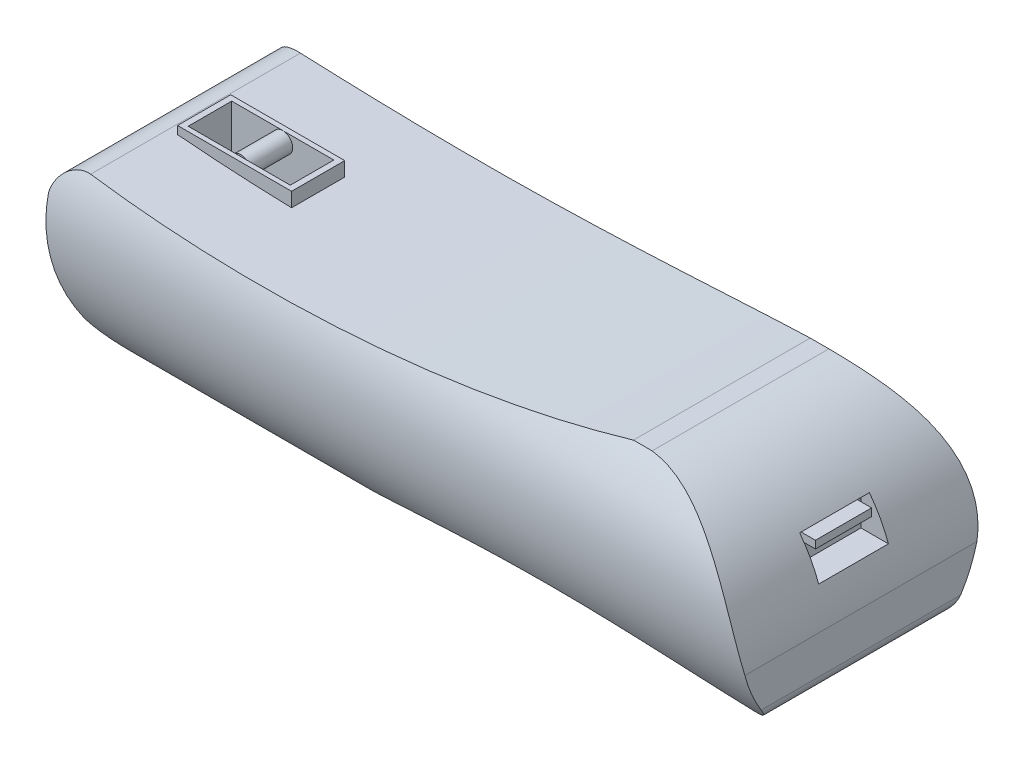
SolidWorks part; units mm, degrees
ref_plane "Front Plane" through (0, 0, 0) normal (0, 0, 1) x (1, 0, 0)
ref_plane "Top Plane" through (0, 0, 0) normal (0, 1, 0) x (1, 0, 0)
ref_plane "Right Plane" through (0, 0, 0) normal (1, 0, 0) x (0, 0, -1)
sketch "Sketch1" plane through (0, 0, 0) normal (0, 1, 0) x (1, 0, 0)
  line L1 (-100, -35) -> (100, -35)
  line L2 (-100, -35) -> (-100, 35)
  line L3 (-100, 35) -> (100, 35)
  line L4 (100, -35) -> (100, 35)
  line L5 (-100, -35) -> (100, 35) construction
  line L6 (-100, 35) -> (100, -35) construction
  point P0 (0, 0)
  dimension "D1" = 70
  dimension "D2" = 200
extrude "Boss-Extrude1" add sketch "Sketch1" along normal blind 50
sketch "Sketch13" plane through (-100, 0, 0) normal (-1, 0, 0) x (0, 0, 1)
  line L0 (-35, 50) -> (35, 50) construction
  line L1 (-35, 0) -> (35, 0) construction
  line L2 (-25.3568, 50) -> (-35, 50)
  line L3 (-35, 50) -> (-35, 0)
  line L4 (-35, 0) -> (-25.3568, 0)
  arc A0 (-25.3568, 50) -> (-25.3568, 0) centre (4.2949, 25) ccw
extrude "Cut-Extrude5" cut sketch "Sketch13" against normal blind 200
mirror "Mirror1" about plane through (0, 0, 0) normal (0, 0, 1) of "Cut-Extrude5"
sketch "Sketch14" plane through (0, 0, 0) normal (0, -1, 0) x (1, 0, 0)
  line L0 (27.5, 0) -> (-27.5, 0) construction
  line L1 (-50.321, 22.5) -> (-50.321, -22.5)
  arc A0 (-50.321, -22.5) -> (-50.321, 22.5) centre (-50.321, 0) ccw
  dimension "D1" = 45
extrude "Cut-Extrude6" cut sketch "Sketch14" against normal blind 5
sketch "Sketch15" plane through (0, 0, 0) normal (0, 0, 1) x (1, 0, 0)
  line L0 (-14.1772, 0) -> (94.7507, 0)
  arc A0 (-14.1772, 0) -> (94.7507, 0) centre (40.2868, -235.9729) cw
extrude "Cut-Extrude7" cut sketch "Sketch15" against normal mid plane 80
sketch "Sketch16" plane through (0, 0, 0) normal (0, 0, 1) x (1, 0, 0)
  line L0 (37.9384, 0) -> (-37.9384, 0) construction
  line L1 (100, 0) -> (100, 50) construction
  line L2 (100, 4.5004) -> (100, 15.4404)
  line L3 (100, 50) -> (-100, 50) construction
  line L4 (-100, 50) -> (-100, 0) construction
  line L5 (-100, 43.8236) -> (-100, 50)
  line L6 (-100, 50) -> (60.0942, 50)
  line L7 (100, 50) -> (100, 15.4404)
  line L8 (100, 0) -> (100, 15.4404)
  line L9 (100, 0) -> (94.4149, 0)
  line L10 (65.4404, 50) -> (100, 50)
  arc A0 (94.4149, 0) -> (100, 4.5004) centre (94.9572, 5.0428) ccw
  arc A1 (100, 15.4404) -> (65.4404, 50) centre (62.7673, 12.7673) ccw
  arc A2 (60.0942, 50) -> (-100, 43.8236) centre (-41.2087, 597.8687) cw
extrude "Cut-Extrude8" cut sketch "Sketch16" against normal mid plane 80 contours A2 L6 L5 | A0 L9 L8 | A1 L10 L7
sketch "Sketch17" plane through (0, 0, 0) normal (0, 0, 1) x (1, 0, 0)
  line L0 (-100, 43.8236) -> (-100, 0) construction
  line L1 (37.9384, 0) -> (-37.9384, 0) construction
  line L2 (-90.4347, 42.892) -> (-105.2215, 46.9203)
  line L3 (-105.2215, 46.9203) -> (-103.8934, 0)
  line L4 (-103.8934, 0) -> (-84.8316, 0)
  arc A0 (-90.4347, 42.892) -> (-100, 35.3271) centre (-91.4349, 34.3269) ccw
  arc A1 (-100, 43.8236) -> (60.0942, 50) centre (-41.2087, 597.8687) ccw construction
  arc A2 (-100, 35.3271) -> (-93.746, 5.3475) centre (-9.5901, 38.5452) ccw
  arc A3 (-93.746, 5.3475) -> (-84.8316, 0) centre (-83.5199, 12.2907) ccw
extrude "Cut-Extrude9" cut sketch "Sketch17" against normal mid plane 80
ref_plane "Plane1" through (110, 0, 0) normal (1, 0, 0) x (0, 0, -1)
sketch "Sketch18" plane through (110, 0, 0) normal (1, 0, 0) x (0, 0, -1)
  line L0 (0, 37.6022) -> (0, -37.6022) construction
  line L1 (-10, 25.4404) -> (10, 25.4404)
  line L2 (-10, 35.4404) -> (-10, 25.4404)
  line L4 (10, 35.4404) -> (10, 25.4404)
  line L8 (-10, 35.4404) -> (10, 35.4404)
  point P0 (0, 20.4404)
  dimension "D1" = 20
extrude "Cut-Extrude10" cut sketch "Sketch18" against normal blind 20
sketch "Sketch20" plane through (90, 0, 0) normal (1, 0, 0) x (0, 0, -1)
  line L0 (0, 37.6022) -> (0, -37.6022) construction
  line L1 (-8.0484, 33.9159) -> (8.0484, 33.9159)
  line L2 (-8.0484, 33.9159) -> (-8.0484, 31.7406)
  line L3 (-8.0484, 31.7406) -> (8.0484, 31.7406)
  line L4 (8.0484, 33.9159) -> (8.0484, 31.7406)
  line L5 (-8.0484, 33.9159) -> (8.0484, 31.7406) construction
  line L6 (-8.0484, 31.7406) -> (8.0484, 33.9159) construction
  point P0 (0, 32.8282)
extrude "Boss-Extrude2" add sketch "Sketch20" along normal blind 5
ref_plane "Plane2" through (0, 25, 0) normal (0, 1, 0) x (1, 0, 0)
sketch "Sketch22" plane through (0, 25, 0) normal (0, 1, 0) x (1, 0, 0)
  line L0 (-37.6022, 0) -> (37.6022, 0) construction
  line L1 (-57.4842, -6.2503) -> (-86.7714, -6.2503)
  line L2 (-57.4842, -6.2503) -> (-57.4842, 6.2503)
  line L3 (-57.4842, 6.2503) -> (-86.7714, 6.2503)
  line L4 (-86.7714, -6.2503) -> (-86.7714, 6.2503)
  line L5 (-57.4842, -6.2503) -> (-86.7714, 6.2503) construction
  line L6 (-57.4842, 6.2503) -> (-86.7714, -6.2503) construction
  point P0 (-72.1278, 0)
extrude "Cut-Extrude11" cut sketch "Sketch22" along normal blind 20
sketch "Sketch23" plane through (0, 25, 0) normal (0, 1, 0) x (1, 0, 0)
  line L1 (-57.4842, 6.2503) -> (-86.7714, 6.2503)
  line L2 (-57.4842, 6.2503) -> (-57.4842, -6.2503)
  line L3 (-57.4842, -6.2503) -> (-86.7714, -6.2503)
  line L4 (-86.7714, 6.2503) -> (-86.7714, -6.2503)
  line L5 (-88.4857, -7.5842) -> (-55.7717, -7.5842)
  line L6 (-88.4857, -7.5842) -> (-88.4857, 7.671)
  line L7 (-88.4857, 7.671) -> (-55.7717, 7.671)
  line L8 (-55.7717, -7.5842) -> (-55.7717, 7.671)
extrude "Boss-Extrude3" add sketch "Sketch23" along normal blind 20
sketch "Sketch25" plane through (0, 0, -6.2503) normal (0, 0, 1) x (1, 0, 0)
  circle A0 centre (-72.1287, 42.15) radius 2.85
extrude "Boss-Extrude4" add sketch "Sketch25" along normal blind 12
ref_plane "Plane3" through (-105, 0, 0) normal (1, 0, 0) x (0, 0, -1)
sketch "Sketch27" plane through (-105, 0, 0) normal (1, 0, 0) x (0, 0, -1)
  line L0 (0, 37.6022) -> (0, -37.6022) construction
  line L3 (-11.1803, 29.9158) -> (11.1803, 29.9158)
  line L4 (-11.1803, 9.9158) -> (11.1803, 9.9158)
  arc A0 (-11.1803, 29.9158) -> (-11.1803, 9.9158) centre (0, 19.9158) ccw
  arc A1 (11.1803, 9.9158) -> (11.1803, 29.9158) centre (0, 19.9158) ccw
  dimension "D1" = 30
extrude "Cut-Extrude12" cut sketch "Sketch27" along normal blind 12.2
sketch "Sketch28" plane through (-92.8, 0, 0) normal (-1, 0, 0) x (0, 0, 1)
  line L0 (-11.1803, 29.9158) -> (-11.1803, 21.9158) construction
  line L1 (-11.1803, 9.9158) -> (-11.1803, 17.9158) construction
  line L2 (-11.1803, 17.9158) -> (-11.1803, 9.9158) construction
  line L5 (-11.1803, 21.9158) -> (-7.1803, 21.9158)
  line L9 (-11.1803, 17.9158) -> (-7.1803, 17.9158)
  line L11 (-11.1803, 21.9158) -> (-11.1803, 17.9158)
  line L12 (-7.1803, 21.9158) -> (-7.1803, 17.9158)
  line L13 (0, -37.6022) -> (0, 37.6022) construction
  line L14 (11.1803, 21.9158) -> (7.1803, 21.9158)
  line L15 (11.1803, 21.9158) -> (11.1803, 17.9158)
  line L16 (11.1803, 17.9158) -> (7.1803, 17.9158)
  line L17 (7.1803, 21.9158) -> (7.1803, 17.9158)
  dimension "D3" = 4
extrude "Cut-Extrude13" cut sketch "Sketch28" against normal blind 20
